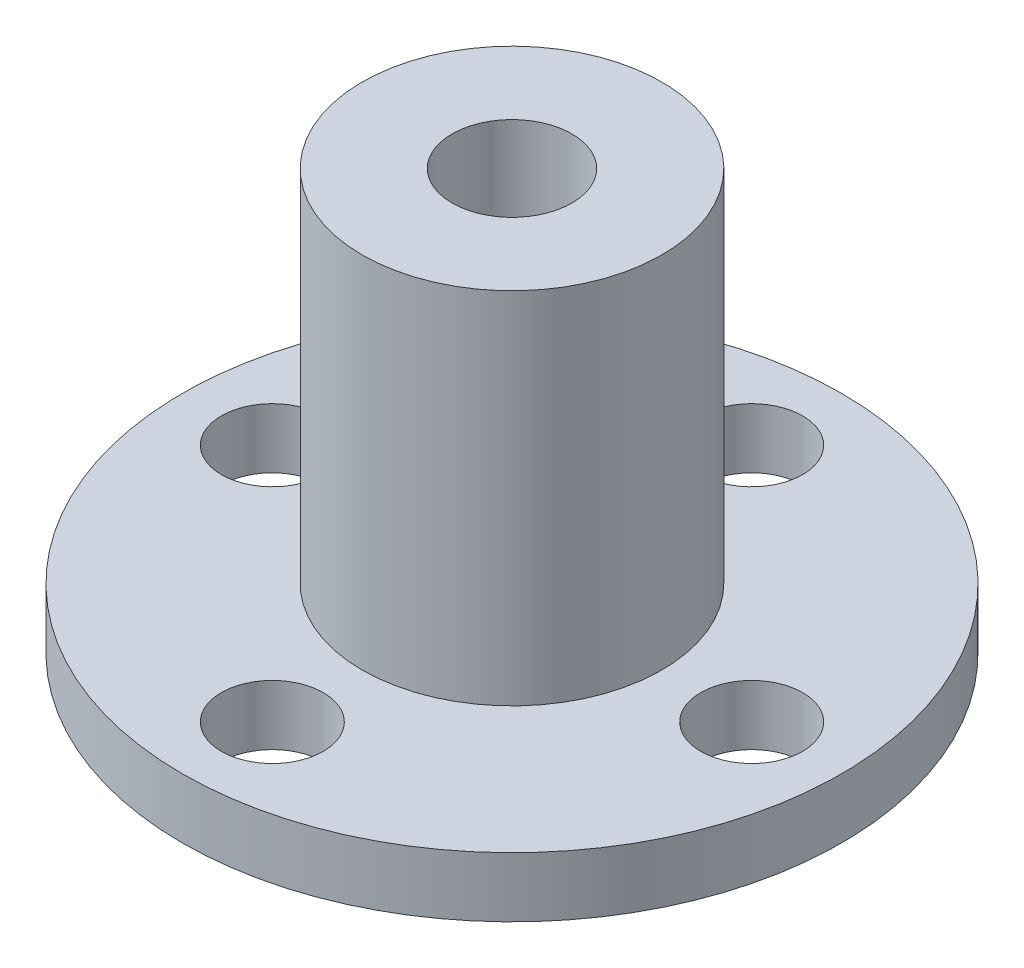
SolidWorks part; units mm, degrees
ref_plane "Front Plane" through (0, 0, 0) normal (0, 0, 1) x (1, 0, 0)
ref_plane "Top Plane" through (0, 0, 0) normal (0, 1, 0) x (1, 0, 0)
ref_plane "Right Plane" through (0, 0, 0) normal (1, 0, 0) x (0, 0, -1)
sketch "Sketch1" plane through (0, 0, 0) normal (0, 1, 0) x (1, 0, 0)
  circle A0 centre (0, 0) radius 11
  dimension "D1" = 22
extrude "Boss-Extrude1" add sketch "Sketch1" along normal blind 2
sketch "Sketch2" plane through (0, 2, 0) normal (0, 1, 0) x (1, 0, 0)
  circle A0 centre (0, 0) radius 5
  dimension "D1" = 10
extrude "Boss-Extrude2" add sketch "Sketch2" along normal blind 12
sketch "Sketch3" plane through (0, 14, 0) normal (0, 1, 0) x (1, 0, 0)
  circle A0 centre (0, 0) radius 2
  dimension "D1" = 4
extrude "Cut-Extrude1" cut sketch "Sketch3" against normal through all
sketch "Sketch4" plane through (0, 2, 0) normal (0, 1, 0) x (1, 0, 0)
  line L0 (0, 8) -> (0, -8) construction
  line L1 (8, 0) -> (-8, 0) construction
  circle A0 centre (0, 8) radius 1.7
  circle A1 centre (8, 0) radius 1.7
  circle A2 centre (0, -8) radius 1.7
  circle A3 centre (-8, 0) radius 1.7
  point P4 (0, 0)
  point P8 (0, 0)
  dimension "D2" = 3.4
  dimension "D1" = 16
extrude "Cut-Extrude2" cut sketch "Sketch4" against normal through all
